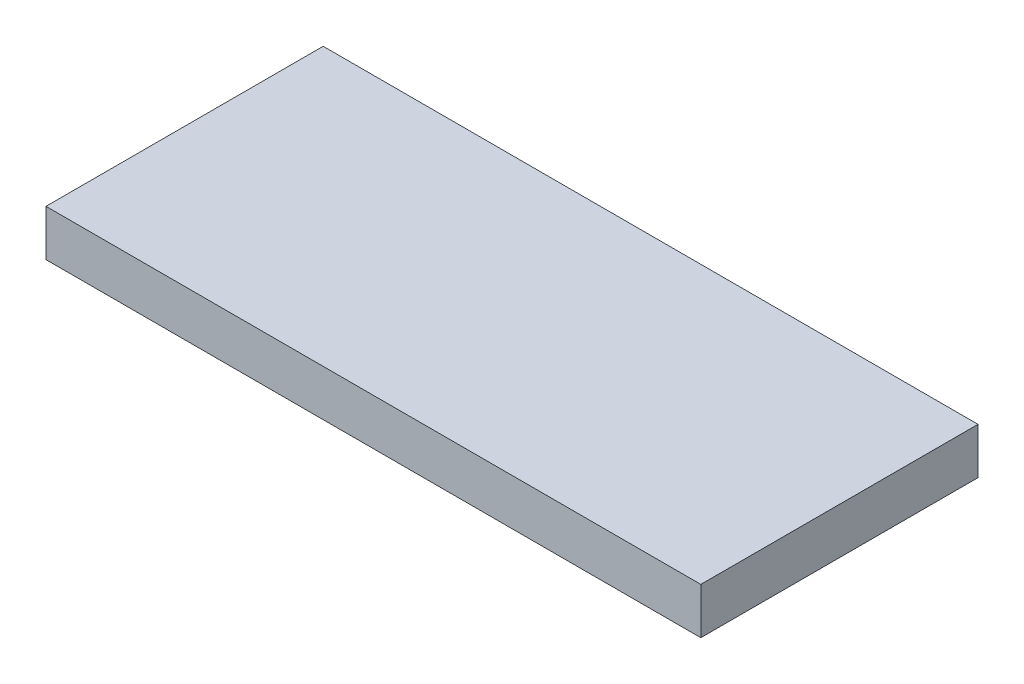
SolidWorks part; units mm, degrees
ref_plane "Alzado" through (0, 0, 0) normal (0, 0, 1) x (1, 0, 0)
ref_plane "Planta" through (0, 0, 0) normal (0, 1, 0) x (1, 0, 0)
ref_plane "Vista lateral" through (0, 0, 0) normal (1, 0, 0) x (0, 0, -1)
sketch "Croquis1" plane through (0, 0, 0) normal (0, 0, 1) x (1, 0, 0)
  line L1 (0, 0) -> (180, 0)
  line L2 (0, 0) -> (0, -12.7)
  line L3 (0, -12.7) -> (180, -12.7)
  line L4 (180, 0) -> (180, -12.7)
  dimension "D1" = 180
  dimension "D2" = 12.7
extrude "Saliente-Extruir1" add sketch "Croquis1" along normal blind 76.2
